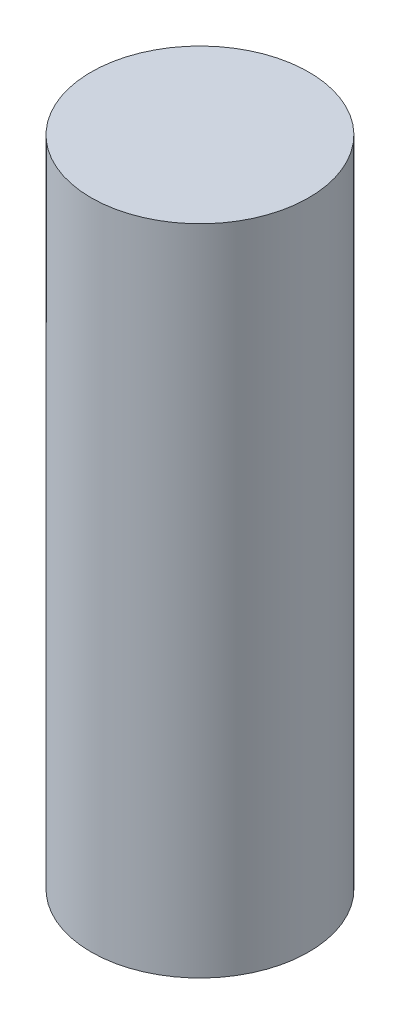
SolidWorks part; units mm, degrees
ref_plane "Front Plane" through (0, 0, 0) normal (0, 0, 1) x (1, 0, 0)
ref_plane "Top Plane" through (0, 0, 0) normal (0, 1, 0) x (1, 0, 0)
ref_plane "Right Plane" through (0, 0, 0) normal (1, 0, 0) x (0, 0, -1)
sketch "Sketch1" plane through (0, 0, 0) normal (0, 1, 0) x (1, 0, 0)
  circle A0 centre (-37.2308, 22.7108) radius 10
extrude "Boss-Extrude1" add sketch "Sketch1" along normal blind 60
